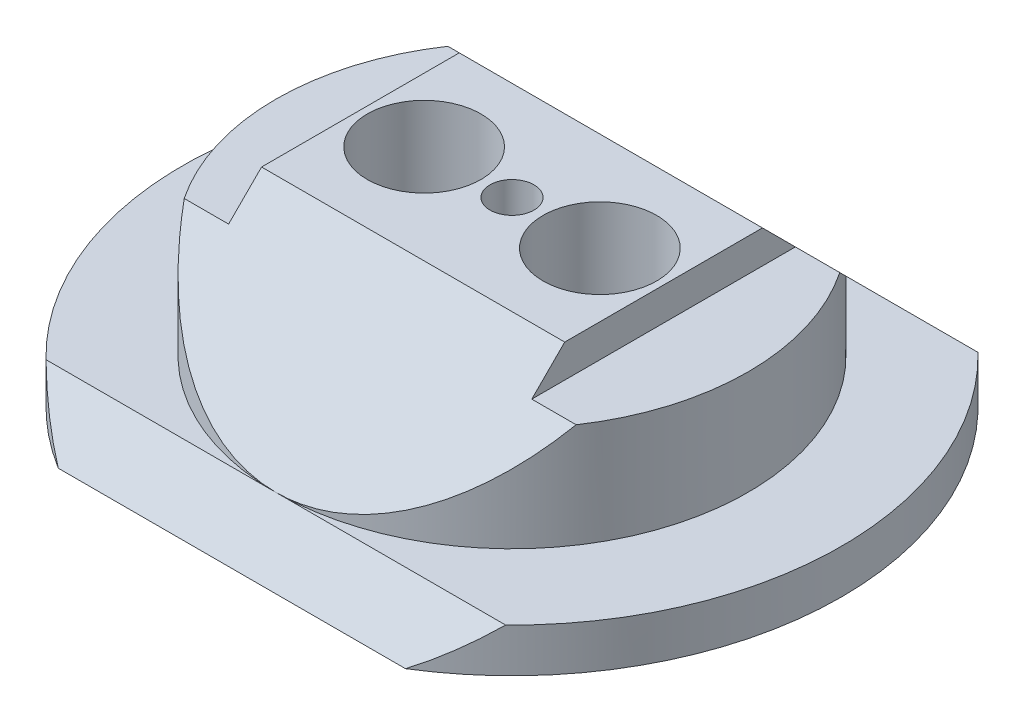
SolidWorks part; units mm, degrees
ref_plane "Front Plane" through (0, 0, 0) normal (0, 0, 1) x (1, 0, 0)
ref_plane "Top Plane" through (0, 0, 0) normal (0, 1, 0) x (1, 0, 0)
ref_plane "Right Plane" through (0, 0, 0) normal (1, 0, 0) x (0, 0, -1)
sketch "Sketch1" plane through (0, 0, 0) normal (0, 1, 0) x (1, 0, 0)
  circle A0 centre (0, 0) radius 30
extrude "Boss-Extrude1" add sketch "Sketch1" along normal blind 4
sketch "Sketch2" plane through (0, 0, 0) normal (1, 0, 0) x (0, 0, -1)
  line L0 (0, 4) -> (21.5, 4)
  line L1 (30, 4) -> (-30, 4) construction
  line L3 (0, 4) -> (-21.5, 4)
  line L5 (0, 4) -> (0, 19.5) construction
  line L6 (-9, 16.5) -> (-21.5, 4)
  line L7 (-9, 16.5) -> (9, 16.5)
  line L9 (9, 16.5) -> (21.5, 4)
  dimension "D1" = 12.5
  dimension "D2" = 45
  dimension "D3" = 21.5
  dimension "D4" = 21.5
  dimension "D5" = 45
sketch "Sketch3" plane through (0, 4, 0) normal (0, 1, 0) x (1, 0, 0)
  circle A0 centre (0, 0) radius 21.5
  dimension "D1" = 43
extrude "Boss-Extrude2" add sketch "Sketch2" along normal up to surface and the other way up to surface up to face at (0, 4, 30) other way up to face at (0, 4, 30)
ref_plane "Plane1" through (0, 12.75, -12.75) normal (0, 0.7071, -0.7071) x (1, 0, 0)
other "SurfaceCut1"
ref_plane "Plane2" through (0, 12.75, 12.75) normal (0, 0.7071, 0.7071) x (1, 0, 0)
other "SurfaceCut2"
extrude "Cut-Extrude2" cut sketch "Sketch3" against normal up to surface (12.5 mm away) flip side to cut contours A0
sketch "Sketch5" plane through (0, 0, 0) normal (0, -1, 0) x (-1, 0, 0)
  line L0 (0, 0) -> (0, -6)
  line L1 (0, -6) -> (-17.5, -6)
  line L2 (-17.5, -6) -> (-17.5, 6)
  line L3 (-17.5, 6) -> (17.5, 6)
  line L4 (17.5, 6) -> (17.5, -6)
  line L5 (17.5, -6) -> (0, -6)
  circle A0 centre (0, 0) radius 6
  circle A1 centre (0, 0) radius 3.5
  dimension "D1" = 12
  dimension "D2" = 7
  dimension "D3" = 12
  dimension "D4" = 6
  dimension "D5" = 35
  dimension "D6" = 17.5
extrude "Boss-Extrude3" add sketch "Sketch5" along normal blind 18 contours L1 L2 L3 L4 L5
sketch "Sketch6" plane through (0, 0, 0) normal (0, -1, 0) x (1, 0, 0)
  line L0 (0, 6) -> (0, 15) construction
  line L1 (-17.5, 6) -> (17.5, 6) construction
  line L2 (0, 15) -> (7, 15)
  line L3 (7, 15) -> (7, 6)
  line L4 (-17.5, 6) -> (17.5, 6) construction
  line L5 (7, 6) -> (-7, 6)
  line L6 (-7, 6) -> (-7, 15)
  line L7 (-7, 15) -> (0, 15)
  dimension "D1" = 14
  dimension "D2" = 9
extrude "Boss-Extrude4" add sketch "Sketch6" along normal blind 15 contours L7 L2 L3 L5 L6
sketch "Sketch7" plane through (0, 0, 0) normal (0, -1, 0) x (1, 0, 0)
  line L0 (0, -6) -> (0, -15) construction
  line L1 (17.5, -6) -> (-17.5, -6) construction
  line L2 (0, -15) -> (7, -15)
  line L3 (7, -15) -> (7, -6)
  line L4 (7, -6) -> (-7, -6)
  line L7 (-7, -6) -> (-7, -15)
  line L8 (-7, -15) -> (0, -15)
  dimension "D1" = 9
  dimension "D2" = 14
extrude "Boss-Extrude5" add sketch "Sketch7" along normal blind 15
sketch "Sketch8" plane through (0, 0, 0) normal (0, 0, 1) x (1, 0, 0)
  line L0 (0, 0) -> (12.5, 0) construction
  line L1 (12.5, 0) -> (12.5, -12.5) construction
  line L2 (12.5, -12.5) -> (-12.5, -12.5) construction
  line L3 (-12.5, -12.5) -> (-12.5, 0) construction
  line L4 (-12.5, 0) -> (0, 0) construction
  circle A0 centre (-12.5, -12.5) radius 2
  circle A1 centre (12.5, -12.5) radius 2
  dimension "D4" = 4
  dimension "D5" = 4
  dimension "D1" = 12.5
  dimension "D2" = 25
  dimension "D3" = 12.5
extrude "Cut-Extrude3" cut sketch "Sketch8" against normal through all both and the other way through all contours A0 | A1
ref_plane "Plane3" through (0, -18, 0) normal (0, -1, 0) x (-1, 0, 0)
ref_plane "Plane4" through (10.366, -9.6749, -8.0624) normal (0.6355, -0.5931, -0.4943) x (-0.3613, 0.3373, -0.8693)
ref_plane "Plane5" through (-10.366, -9.6749, -8.0624) normal (0.6355, 0.5931, 0.4943) x (0.3613, 0.3373, -0.8693)
ref_plane "Plane6" through (10.366, -9.6749, 8.0624) normal (-0.6355, 0.5931, -0.4943) x (-0.3613, 0.3373, 0.8693)
ref_plane "Plane7" through (-10.366, -9.6749, 8.0624) normal (0.6355, 0.5931, -0.4943) x (-0.3613, -0.3373, -0.8693)
ref_plane "Plane9" through (0, 0, 6) normal (0, 0, 1) x (1, 0, 0)
sketch "Sketch16" plane through (0, 0, 6) normal (0, 0, 1) x (1, 0, 0)
  line L0 (17.5, -18) -> (17.5, -14.5)
  line L1 (-6.6, -18) -> (6.6, -18) construction
  line L2 (17.5, -18) -> (17.5, 0) construction
  line L3 (17.5, -18) -> (14, -18)
  line L4 (17.5, -14.5) -> (14, -18)
  line L5 (-17.5, -18) -> (-14, -18)
  line L6 (-17.5, -18) -> (-17.5, 0) construction
  line L7 (-14, -18) -> (-17.5, -14.5)
  line L8 (-17.5, -14.5) -> (-17.5, -18)
  dimension "D2" = 3.5
extrude "Cut-Extrude8" cut sketch "Sketch16" against normal through all both and the other way through all
sketch "Sketch17" plane through (10.366, -9.6749, -8.0624) normal (0.6355, -0.5931, -0.4943) x (-0.3613, 0.3373, -0.8693)
  line L0 (-2.3725, -6.1896) -> (7.9806, -0.7067)
  line L1 (5.4512, -6.1896) -> (10.5101, 4.7762) construction
  line L2 (7.9806, -0.7067) -> (7.9806, -10.9658)
  line L3 (10.5101, -15.7421) -> (5.4512, -6.1896) construction
  line L4 (7.9806, -10.9658) -> (-2.3725, -6.1896)
extrude "Cut-Extrude9" cut sketch "Sketch17" along normal through all
sketch "Sketch19" plane through (-10.366, -9.6749, -8.0624) normal (0.6355, 0.5931, 0.4943) x (0.3613, 0.3373, -0.8693)
  line L0 (-2.3725, -6.1896) -> (7.9806, -10.9658)
  line L1 (7.9806, -10.9658) -> (7.9806, -0.7067)
  line L2 (5.4512, -6.1896) -> (10.5101, 4.7762) construction
  line L3 (7.9806, -0.7067) -> (-2.3725, -6.1896)
extrude "Cut-Extrude11" cut sketch "Sketch19" against normal blind 20 contours L3 L0 L1
sketch "Sketch20" plane through (-10.366, -9.6749, 8.0624) normal (0.6355, 0.5931, -0.4943) x (-0.3613, -0.3373, -0.8693)
  line L0 (2.3725, -6.1896) -> (-7.9806, -0.7067)
  line L1 (-5.4512, -6.1896) -> (-10.5101, 4.7762) construction
  line L2 (-7.9806, -0.7067) -> (-7.9806, -10.9658)
  line L3 (-5.4512, -6.1896) -> (-10.5101, -15.7421) construction
  line L4 (-7.9806, -10.9658) -> (2.3725, -6.1896)
extrude "Cut-Extrude12" cut sketch "Sketch20" against normal blind 20
sketch "Sketch21" plane through (10.366, -9.6749, 8.0624) normal (-0.6355, 0.5931, -0.4943) x (-0.3613, 0.3373, 0.8693)
  line L0 (-2.3725, -6.1896) -> (7.9806, -0.7067)
  line L1 (5.4512, -6.1896) -> (10.5101, 4.7762) construction
  line L2 (7.9806, -0.7067) -> (7.9806, -10.9658)
  line L3 (7.9806, -10.9658) -> (-2.3725, -6.1896)
extrude "Cut-Extrude13" cut sketch "Sketch21" against normal blind 20 contours L0 L2 L3
ref_plane "Plane10" through (0, 16.5, 0) normal (0, 1, 0) x (1, 0, 0)
sketch "Sketch25" plane through (0, 0, 0) normal (0, 0, 1) x (1, 0, 0)
  line L1 (-33.0377, 0) -> (33.0377, 0)
  line L2 (-33.0377, 0) -> (-33.0377, -20.1422)
  line L3 (-33.0377, -20.1422) -> (33.0377, -20.1422)
  line L4 (33.0377, 0) -> (33.0377, -20.1422)
  dimension "D1" = 20.1422
  dimension "D2" = 66.0754
extrude "Cut-Extrude14" cut sketch "Sketch25" along normal through all both and the other way through all
sketch "Sketch26" plane through (0, 16.5, 0) normal (0, 1, 0) x (1, 0, 0)
  line L0 (-9.075, 0) -> (9.075, 0) construction
  circle A0 centre (-8, 0) radius 5.175
  circle A2 centre (8, 0) radius 5.175
  dimension "D1" = 10.35
  dimension "D2" = 10.35
  dimension "D3" = 8
  dimension "D4" = 8
extrude "Cut-Extrude15" cut sketch "Sketch26" against normal blind 24
sketch "Sketch29" plane through (0, 0, 6) normal (0, 0, 1) x (1, 0, 0)
  line L0 (21.5, 4) -> (21.5, 16.5) construction
  line L1 (21.5, 13.5) -> (13.8, 13.5)
  line L2 (21.5, 13.5) -> (21.5, 16.5)
  line L3 (21.5, 16.5) -> (13.8, 16.5)
  line L4 (13.8, 13.5) -> (13.8, 16.5)
  line L5 (9.9, 16.5) -> (-9.9, 16.5) construction
  dimension "D1" = 3
  dimension "D2" = 7.7
extrude "Cut-Extrude17" cut sketch "Sketch29" against normal through all both and the other way through all
sketch "Sketch31" plane through (0, 0, 6) normal (0, 0, 1) x (1, 0, 0)
  line L0 (-21.5, 16.5) -> (-21.5, 4) construction
  line L1 (-21.5, 13.5) -> (-13.8, 13.5)
  line L2 (-21.5, 13.5) -> (-21.5, 16.5)
  line L3 (-21.5, 16.5) -> (-13.8, 16.5)
  line L4 (-13.8, 13.5) -> (-13.8, 16.5)
  line L5 (9.9, 16.5) -> (-9.9, 16.5) construction
  dimension "D1" = 3
  dimension "D2" = 7.7
extrude "Cut-Extrude18" cut sketch "Sketch31" against normal through all both and the other way through all
sketch "Sketch34" plane through (0, 0, 0) normal (0, -1, 0) x (1, 0, 0)
  circle A0 centre (0, 0) radius 1.375
  dimension "D1" = 2.75
extrude "Cut-Extrude21" cut sketch "Sketch34" against normal blind 20
sketch "Sketch35" plane through (0, 16.5, 0) normal (0, 1, 0) x (1, 0, 0)
  circle A0 centre (0, 0) radius 2
  dimension "D1" = 4
extrude "Cut-Extrude22" cut sketch "Sketch35" against normal blind 6
sketch "Sketch37" plane through (0, 0, 0) normal (0, -1, 0) x (1, 0, 0)
  line L0 (0, -9.075) -> (0, 9.075) construction
  line L1 (9.075, 0) -> (-9.075, 0) construction
  circle A0 centre (0, -15) radius 5
  circle A1 centre (0, 15) radius 5
  circle A2 centre (-22, 0) radius 5
  circle A3 centre (22, 0) radius 5
  circle A4 centre (-14, 12) radius 5
  circle A5 centre (14, 12) radius 5
  circle A6 centre (-14, -12) radius 5
  circle A7 centre (14, -12) radius 5
  dimension "D1" = 10
  dimension "D2" = 10
  dimension "D3" = 10
  dimension "D4" = 10
  dimension "D10" = 10
  dimension "D14" = 10
  dimension "D15" = 10
  dimension "D16" = 10
  dimension "D5" = 15
  dimension "D6" = 15
  dimension "D7" = 22
  dimension "D8" = 22
  dimension "D9" = 14
  dimension "D11" = 12
  dimension "D12" = 12
  dimension "D13" = 14
  dimension "D17" = 12
  dimension "D18" = 14
  dimension "D19" = 14
  dimension "D20" = 12
extrude "Cut-Extrude23" cut sketch "Sketch37" against normal blind 3
